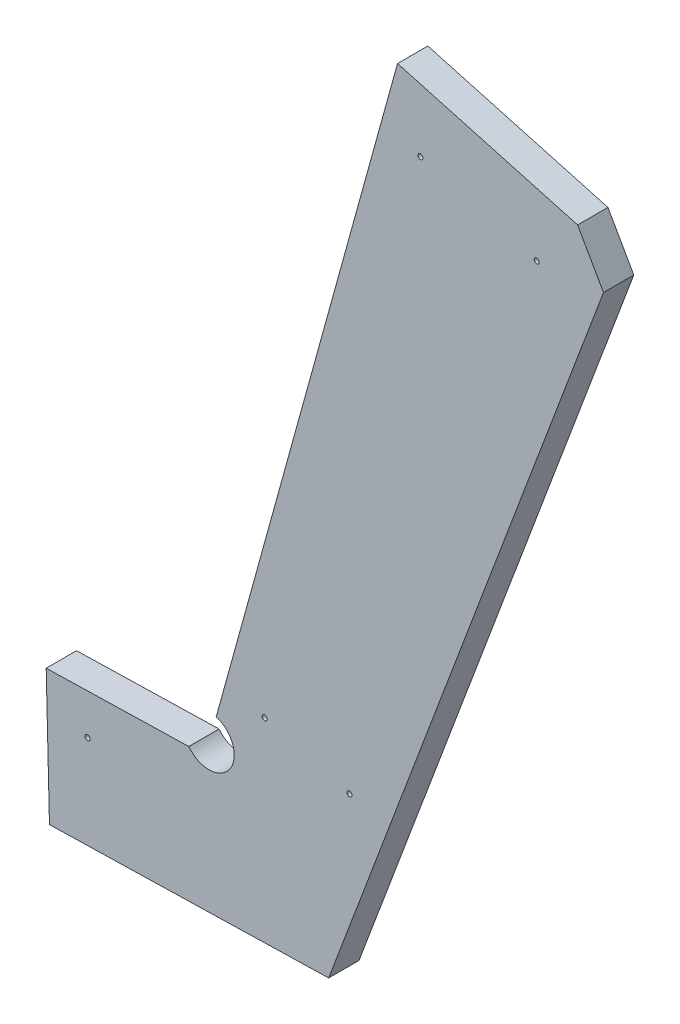
SolidWorks part; units mm, degrees
material "Beech"
ref_plane "Front Plane" through (0, 0, 0) normal (0, 0, 1) x (1, 0, 0)
ref_plane "Top Plane" through (0, 0, 0) normal (0, 1, 0) x (1, 0, 0)
ref_plane "Right Plane" through (0, 0, 0) normal (1, 0, 0) x (0, 0, -1)
sketch "Sketch1" plane through (0, 0, 0) normal (0, 0, 1) x (1, 0, 0)
  line L0 (-45.6457, -462.2836) -> (-43.5919, -546.3964)
  line L1 (-43.5919, -546.3964) -> (131.8459, -542.1127)
  line L2 (-43.5919, -546.3964) -> (-42.1969, -603.5294) construction
  line L3 (131.8459, -542.1127) -> (304.502, -82.7999)
  line L12 (288.249, -54.1429) -> (175.0934, -22.8896)
  line L13 (175.0934, -22.8896) -> (61.1778, -435.3327)
  line L14 (43.9506, -460.0959) -> (-45.6457, -462.2836)
  line L16 (-42.1969, -603.5294) -> (110.1577, -599.8093) construction
  line L17 (110.1577, -599.8093) -> (131.8459, -542.1127) construction
  line L37 (304.502, -82.7999) -> (288.249, -54.1429)
  arc A2 (43.9506, -460.0959) -> (61.1778, -435.3327) centre (56.6289, -450.542) ccw
  point P8 (123.5388, -564.212)
  point P10 (-43.5919, -544.2545)
  point P11 (131.8459, -534.5612)
  dimension "D2" = 152.4
  dimension "D1" = 57.15
extrude "Boss-Extrude1" add sketch "Sketch1" along normal blind 19.05
hole_wizard "Hole1" positions "Sketch2" profile "Sketch3" legacy
sketch "Sketch2" plane through (162.2459, -21.7021, -146.425) normal (-0.9639, 0.2662, 0) x (0, 0, -1)
  line L8 (155.95, -2.2757) -> (155.95, 437.7664) construction
  line L11 (175, -2.2757) -> (175, 437.7664) construction
  line L15 (155.95, -2.2757) -> (155.95, 107.7348)
  line L16 (155.95, 107.7348) -> (155.95, 217.7454)
  line L17 (155.95, 217.7454) -> (155.95, 327.7559)
  line L18 (155.95, 327.7559) -> (155.95, 437.7664)
  line L20 (175, -2.2757) -> (175, 85.7327)
  line L21 (175, 85.7327) -> (175, 173.7411)
  line L22 (175, 173.7411) -> (175, 261.7496)
  line L23 (175, 261.7496) -> (175, 349.758)
  line L24 (175, 349.758) -> (175, 437.7664)
  line L25 (0, 155.0243) -> (0, 437.7664) construction
  point P36 (155.95, 107.7348)
  point P40 (155.95, 327.7559)
  point P46 (175, 85.7327)
  point P52 (175, 349.758)
  point P77 (-175, 349.758)
  point P80 (-175, 85.7327)
  point P81 (-155.95, 327.7559)
  point P83 (-155.95, 107.7348)
sketch "Sketch3" plane through (133.5638, -125.5487, 9.525) normal (0, 0, 1) x (-0.2662, -0.9639, 0)
  line L0 (0, 0) -> (0, 32.7039)
  line L1 (0, 32.7039) -> (1.5875, 31.75)
  line L2 (1.5875, 31.75) -> (1.5875, 4.0177)
  line L3 (1.5875, 4.0177) -> (5.08, 0)
  line L4 (5.08, 0) -> (0, 0)
  line L5 (0, -14.3089) -> (0, 102.4216) construction
  line L6 (0, 32.7039) -> (-1.5875, 31.75) construction
  line L7 (-1.5875, 4.0177) -> (-5.08, 0) construction
  dimension "Diameter" = 3.175
  dimension "Depth" = 31.75
  dimension "C-Sink Diameter" = 10.16
  dimension "C-Sink Angle" = 82
  dimension "Drill Angle" = 118
hole_wizard "Hole2" positions "Sketch4" profile "Sketch5" legacy
sketch "Sketch4" plane through (162.2459, -21.7021, 165.475) normal (-0.9639, 0.2662, 0) x (0, 0, -1)
  line L8 (155.95, -2.2757) -> (155.95, 437.7664) construction
  line L11 (175, -2.2757) -> (175, 437.7664) construction
  line L15 (155.95, -2.2757) -> (155.95, 107.7348)
  line L16 (155.95, 107.7348) -> (155.95, 217.7454)
  line L17 (155.95, 217.7454) -> (155.95, 327.7559)
  line L18 (155.95, 327.7559) -> (155.95, 437.7664)
  line L20 (175, -2.2757) -> (175, 85.7327)
  line L21 (175, 85.7327) -> (175, 173.7411)
  line L22 (175, 173.7411) -> (175, 261.7496)
  line L23 (175, 261.7496) -> (175, 349.758)
  line L24 (175, 349.758) -> (175, 437.7664)
  line L25 (0, 155.0243) -> (0, 437.7664) construction
  point P36 (155.95, 107.7348)
  point P40 (155.95, 327.7559)
  point P46 (175, 85.7327)
  point P52 (175, 349.758)
  point P77 (-175, 349.758)
  point P80 (-175, 85.7327)
  point P81 (-155.95, 327.7559)
  point P83 (-155.95, 107.7348)
sketch "Sketch5" plane through (133.5638, -125.5487, 321.425) normal (0, 0, 1) x (-0.2662, -0.9639, 0)
  line L0 (0, 0) -> (0, 32.7039)
  line L1 (0, 32.7039) -> (1.5875, 31.75)
  line L2 (1.5875, 31.75) -> (1.5875, 4.0177)
  line L3 (1.5875, 4.0177) -> (5.08, 0)
  line L4 (5.08, 0) -> (0, 0)
  line L5 (0, -14.3089) -> (0, 102.4216) construction
  line L6 (0, 32.7039) -> (-1.5875, 31.75) construction
  line L7 (-1.5875, 4.0177) -> (-5.08, 0) construction
  dimension "Diameter" = 3.175
  dimension "Depth" = 31.75
  dimension "C-Sink Diameter" = 10.16
  dimension "C-Sink Angle" = 82
  dimension "Drill Angle" = 118
hole_wizard "Hole3" positions "Sketch6" profile "Sketch7" legacy
sketch "Sketch6" plane through (311.9283, -63.0439, -19.05) normal (0, 0, -1) x (-0.3519, -0.9361, 0)
  line L0 (48.5061, 138.7859) -> (35.9701, 0) construction
  line L5 (414.5728, 105.7206) -> (405.0235, 0) construction
  line L7 (490.0108, 170.6797) -> (621.0107, 117.7523) construction
  line L12 (503.094, 203.0616) -> (634.0938, 150.1342) construction
  line L16 (586.8736, 410.4234) -> (717.8734, 357.496) construction
  line L19 (597.4602, 127.2674) -> (610.5433, 159.6493) construction
  line L20 (610.5433, 159.6493) -> (694.3229, 367.011) construction
  line L22 (513.5613, 161.1647) -> (526.6445, 193.5466) construction
  line L23 (526.6445, 193.5466) -> (610.424, 400.9084) construction
  point P0 (46.2211, 113.4889)
  point P2 (39.3976, 37.9455)
  point P4 (412.2879, 80.4236)
  point P51 (407.3085, 25.297)
  point P56 (513.5613, 161.1647)
  point P58 (597.4602, 127.2674)
  point P61 (610.5433, 159.6493)
  point P63 (694.3229, 367.011)
  point P66 (526.6445, 193.5466)
  point P68 (610.424, 400.9084)
sketch "Sketch7" plane through (189.4334, -66.3768, -19.05) normal (1, 0, 0) x (0, 1, 0)
  line L0 (0, 0) -> (0, 39.0539)
  line L1 (0, 39.0539) -> (1.5875, 38.1)
  line L2 (1.5875, 38.1) -> (1.5875, 4.0177)
  line L3 (1.5875, 4.0177) -> (5.08, 0)
  line L4 (5.08, 0) -> (0, 0)
  line L5 (0, -14.3089) -> (0, 102.4216) construction
  line L6 (0, 39.0539) -> (-1.5875, 38.1) construction
  line L7 (-1.5875, 4.0177) -> (-5.08, 0) construction
  dimension "Diameter" = 3.175
  dimension "Depth" = 38.1
  dimension "C-Sink Diameter" = 10.16
  dimension "C-Sink Angle" = 82
  dimension "Drill Angle" = 118
